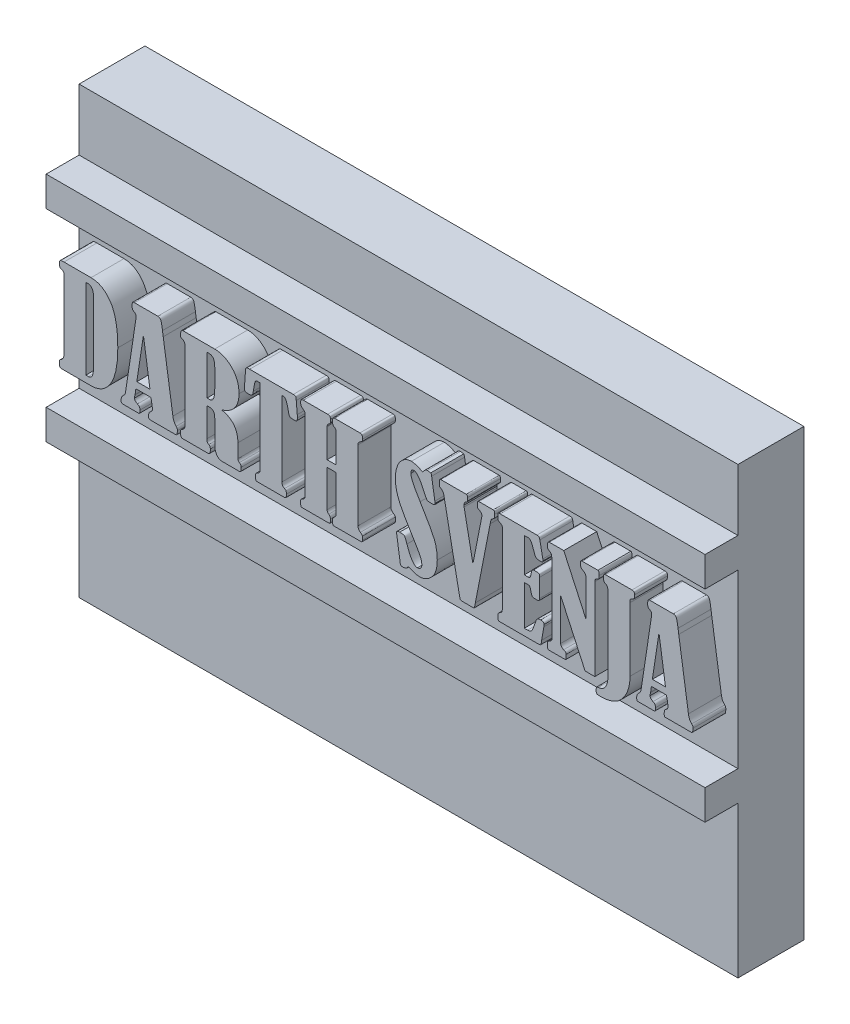
SolidWorks part; units mm, degrees
ref_plane "Plan de face" through (0, 0, 0) normal (0, 0, 1) x (1, 0, 0)
ref_plane "Plan de dessus" through (0, 0, 0) normal (0, 1, 0) x (1, 0, 0)
ref_plane "Plan de droite" through (0, 0, 0) normal (1, 0, 0) x (0, 0, -1)
sketch "Esquisse1" plane through (0, 0, 0) normal (0, 0, 1) x (1, 0, 0)
  line L1 (-20, -13.5) -> (20, -13.5)
  line L2 (-20, -13.5) -> (-20, 13.5)
  line L3 (-20, 13.5) -> (20, 13.5)
  line L4 (20, -13.5) -> (20, 13.5)
  line L5 (-20, -13.5) -> (20, 13.5) construction
  line L6 (-20, 13.5) -> (20, -13.5) construction
  point P0 (0, 0)
  dimension "D1" = 27
  dimension "D2" = 40
extrude "Boss.-Extru.1" add sketch "Esquisse1" along normal blind 4
sketch "Esquisse2" plane through (0, 0, 4) normal (0, 0, 1) x (1, 0, 0)
  text T0 "DARTH SVENJA" font "Bernard MT Condensed" height in points 20
extrude "Boss.-Extru.2" add sketch "Esquisse2" along normal blind 2
sketch "Esquisse3" plane through (0, 0, 4) normal (0, 0, 1) x (1, 0, 0)
  line L0 (20, -13.5) -> (20, 13.5) construction
  line L1 (-20, 9.7657) -> (20, 9.7657)
  line L2 (-20, 9.7657) -> (-20, 7.9488)
  line L3 (-20, 7.9488) -> (20, 7.9488)
  line L4 (20, 9.7657) -> (20, 7.9488)
  line L5 (-20, 9.7657) -> (20, 7.9488) construction
  line L6 (-20, 7.9488) -> (20, 9.7657) construction
  point P0 (0, 8.8573)
extrude "Boss.-Extru.3" add sketch "Esquisse3" along normal blind 2
pattern_linear "Répétition linéaire1" count 2 spacing 12.26 along (0, -1, 0) of "Boss.-Extru.3"
